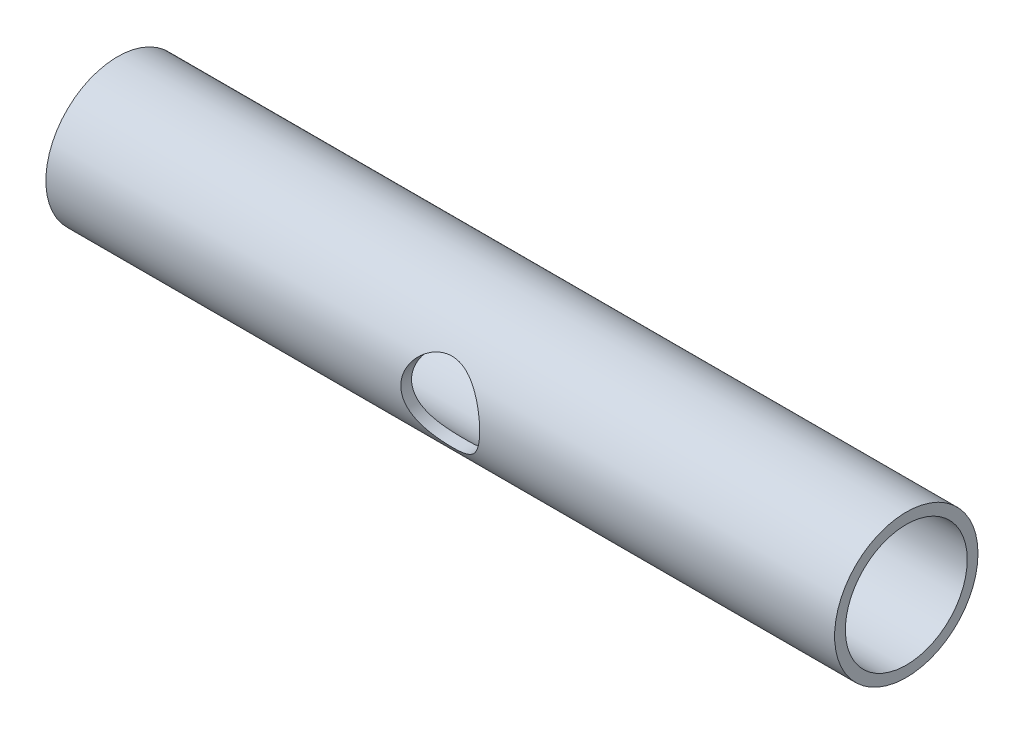
SolidWorks part; units mm, degrees
ref_plane "前视基准面" through (0, 0, 0) normal (0, 0, 1) x (1, 0, 0)
ref_plane "上视基准面" through (0, 0, 0) normal (0, 1, 0) x (1, 0, 0)
ref_plane "右视基准面" through (0, 0, 0) normal (1, 0, 0) x (0, 0, -1)
sketch "草图1" plane through (0, 0, 0) normal (1, 0, 0) x (0, 0, -1)
  circle A0 centre (0, 0) radius 10
  circle A1 centre (0, 0) radius 8.5
  dimension "D1" = 20
  dimension "D2" = 17
extrude "凸台-拉伸1" add sketch "草图1" along normal blind 110
sketch "草图2" plane through (0, 0, 0) normal (0, 0, 1) x (1, 0, 0)
  line L0 (0, 0) -> (110, 0) construction
  line L1 (110, -10) -> (110, 10) construction
  circle A0 centre (55, 0) radius 5.5
  dimension "D1" = 11
extrude "切除-拉伸1" cut sketch "草图2" against normal through all both and the other way through all
